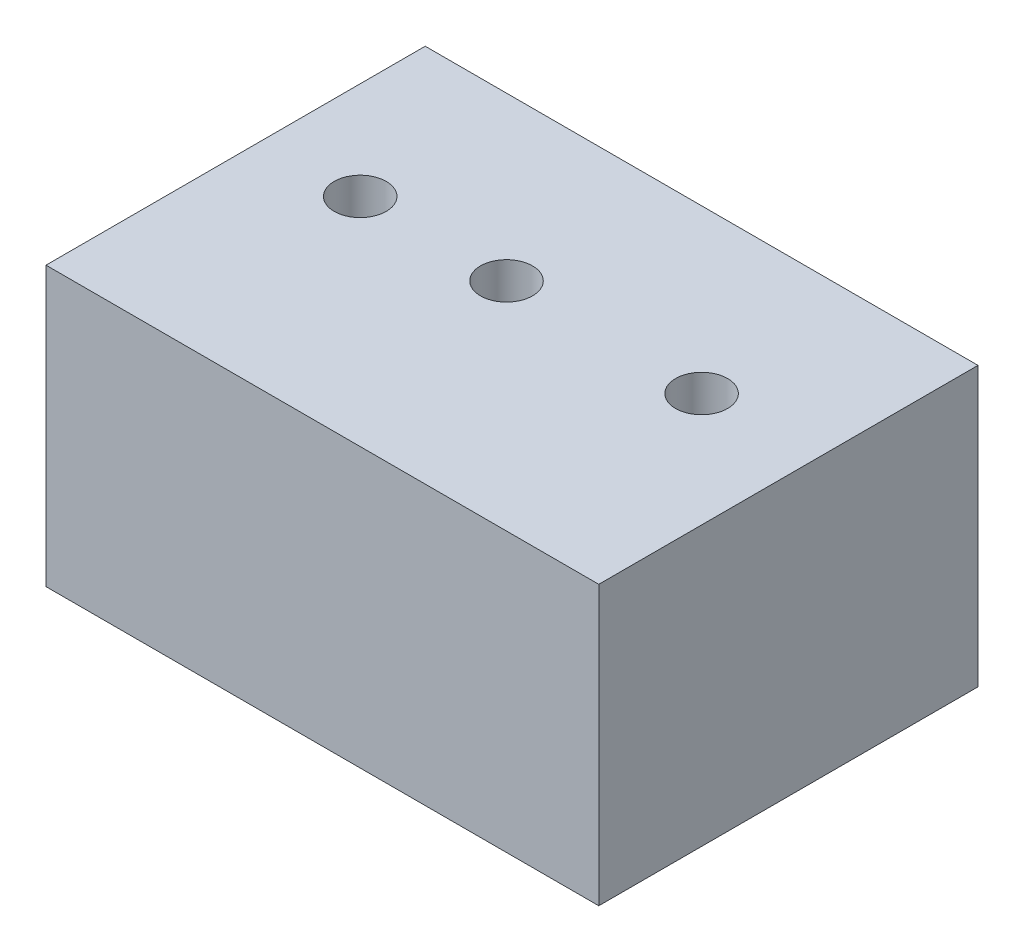
SolidWorks part; units mm, degrees
ref_plane "Front Plane" through (0, 0, 0) normal (0, 0, 1) x (1, 0, 0)
ref_plane "Top Plane" through (0, 0, 0) normal (0, 1, 0) x (1, 0, 0)
ref_plane "Right Plane" through (0, 0, 0) normal (1, 0, 0) x (0, 0, -1)
sketch "Sketch1" plane through (0, 0, 0) normal (0, 1, 0) x (1, 0, 0)
  line L1 (0, 0) -> (34, 0)
  line L2 (0, 0) -> (0, 23.325)
  line L3 (0, 23.325) -> (34, 23.325)
  line L4 (34, 0) -> (34, 23.325)
  circle A0 centre (6, 13.325) radius 1.6
  circle A1 centre (15, 13.325) radius 1.6
  circle A2 centre (27, 13.325) radius 1.6
  point P13 (23.4598, 7.9598)
  dimension "D2" = 3.2
  dimension "D8" = 3.2
  dimension "D9" = 3.2
  dimension "D1" = 13.325
  dimension "D3" = 34
  dimension "D4" = 6
  dimension "D5" = 23.325
  dimension "D6" = 9
  dimension "D7" = 12
extrude "Boss-Extrude1" add sketch "Sketch1" along normal blind 17.125
equation "\"m3\"= 3.2"
equation "\"D2@Sketch1\"=\"m3\""
equation "\"D9@Sketch1\"=\"m3\""
equation "\"D8@Sketch1\"=\"m3\""
